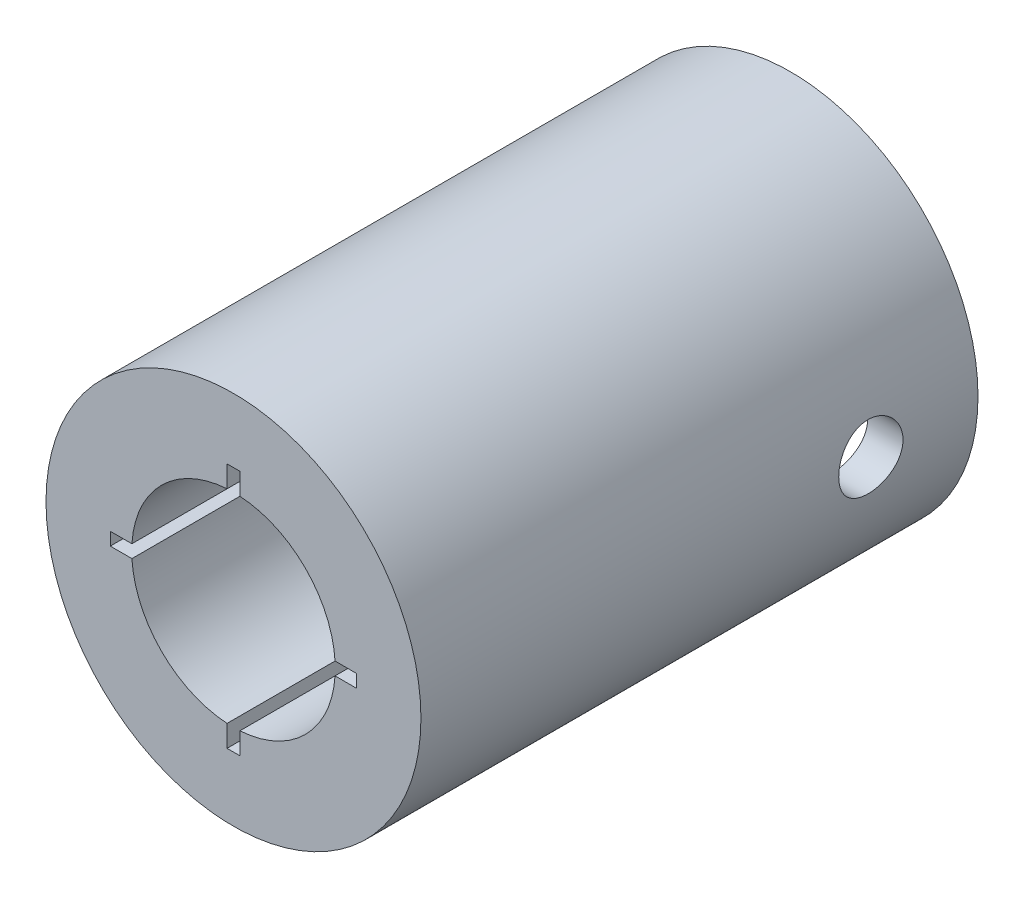
SolidWorks part; units mm, degrees
ref_plane "前视基准面" through (0, 0, 0) normal (0, 0, 1) x (1, 0, 0)
ref_plane "上视基准面" through (0, 0, 0) normal (0, 1, 0) x (1, 0, 0)
ref_plane "右视基准面" through (0, 0, 0) normal (1, 0, 0) x (0, 0, -1)
sketch "草图1" plane through (0, 0, 0) normal (0, 0, 1) x (1, 0, 0)
  circle A0 centre (0, 0) radius 7.1
  circle A1 centre (0, 0) radius 8.75
  dimension "D1" = 14.2
  dimension "D2" = 17.5
extrude "凸台-拉伸1" add sketch "草图1" along normal blind 10
sketch "草图2" plane through (0, 0, 0) normal (1, 0, 0) x (0, 0, -1)
  line L0 (-10, 8.75) -> (-10, -8.75) construction
  line L1 (0, 8.75) -> (-10, 8.75) construction
  circle A0 centre (-5, 0) radius 1.5
  dimension "D1" = 3
  dimension "D2" = 5
  dimension "D3" = 8.75
extrude "切除-拉伸1" cut sketch "草图2" along normal blind 20 and the other way blind 10
sketch "草图3" plane through (0, 0, 10) normal (0, 0, 1) x (1, 0, 0)
  circle A0 centre (0, 0) radius 4.75
  circle A1 centre (0, 0) radius 8.75
  dimension "D1" = 9.5
  dimension "D2" = 17.5
extrude "凸台-拉伸2" add sketch "草图3" along normal blind 16
sketch "草图4" plane through (0, 0, 26) normal (0, 0, 1) x (1, 0, 0)
  line L0 (0, 0) -> (0, -4.75) construction
  line L1 (-4.75, 0) -> (4.75, 0) construction
  line L2 (-0.3, -4.7405) -> (-0.3, -5.75)
  line L3 (-0.3, -5.75) -> (0.3, -5.75)
  line L4 (0.3, -5.75) -> (0.3, -4.7405)
  line L5 (-5.75, -0.3) -> (-4.7405, -0.3)
  line L6 (-4.7405, 0.3) -> (-5.75, 0.3)
  line L7 (-5.75, 0.3) -> (-5.75, -0.3)
  line L8 (-0.3, 5.75) -> (-0.3, 4.7405)
  line L9 (0.3, 4.7405) -> (0.3, 5.75)
  line L10 (0.3, 5.75) -> (-0.3, 5.75)
  line L11 (5.75, 0.3) -> (4.7405, 0.3)
  line L12 (4.7405, -0.3) -> (5.75, -0.3)
  line L13 (5.75, -0.3) -> (5.75, 0.3)
  circle A0 centre (0, 0) radius 4.75 construction
  arc A1 (-0.3, -4.7405) -> (0.3, -4.7405) centre (0, 0) ccw
  arc A2 (-4.7405, 0.3) -> (-4.7405, -0.3) centre (0, 0) ccw
  arc A3 (0.3, 4.7405) -> (-0.3, 4.7405) centre (0, 0) ccw
  arc A4 (4.7405, -0.3) -> (4.7405, 0.3) centre (0, 0) ccw
  point P26 (0, 0)
  dimension "D1" = 0.6
  dimension "D2" = 0.3
  dimension "D3" = 11.5
  dimension "D4" = 4
extrude "切除-拉伸2" cut sketch "草图4" against normal blind 8
